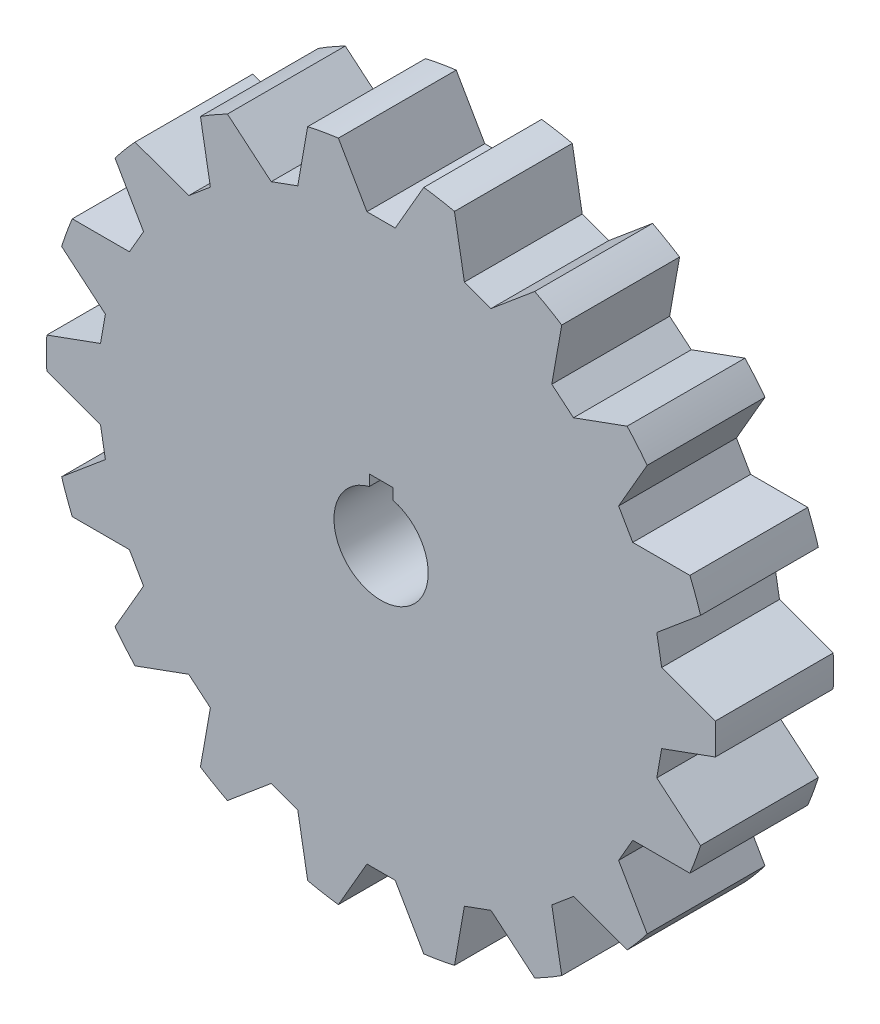
SolidWorks part; units mm, degrees
ref_plane "Front Plane" through (0, 0, 0) normal (0, 0, 1) x (1, 0, 0)
ref_plane "Top Plane" through (0, 0, 0) normal (0, 1, 0) x (1, 0, 0)
ref_plane "Right Plane" through (0, 0, 0) normal (1, 0, 0) x (0, 0, -1)
sketch "Sketch1" plane through (0, 0, 0) normal (0, 0, 1) x (1, 0, 0)
  line L0 (2.5, 9.6825) -> (2.5, 12)
  line L1 (2.5, 12) -> (-2.5, 12)
  line L8 (-2.5, 12) -> (-2.5, 9.6825)
  line L9 (-3, 59.925) -> (3, 59.925)
  line L10 (3, 59.925) -> (9.0591, 70.4197)
  line L12 (-9.0591, 70.4197) -> (-3, 59.925)
  line L13 (23.3146, 55.285) -> (32.5978, 63.0745)
  line L14 (15.5721, 69.2713) -> (17.6765, 57.3371)
  line L15 (17.6765, 57.3371) -> (23.3146, 55.285)
  line L16 (40.8172, 43.9768) -> (52.2046, 48.1215)
  line L17 (38.3252, 59.7677) -> (36.2209, 47.8335)
  line L18 (36.2209, 47.8335) -> (40.8172, 43.9768)
  line L19 (53.3965, 27.3644) -> (65.5148, 27.3644)
  line L20 (56.4557, 43.0553) -> (50.3965, 32.5606)
  line L21 (50.3965, 32.5606) -> (53.3965, 27.3644)
  line L22 (59.5355, 7.4514) -> (70.923, 3.3067)
  line L23 (67.7767, 21.1498) -> (58.4936, 13.3603)
  line L24 (58.4936, 13.3603) -> (59.5355, 7.4514)
  line L25 (58.4936, -13.3603) -> (67.7767, -21.1498)
  line L26 (70.923, -3.3067) -> (59.5355, -7.4514)
  line L27 (59.5355, -7.4514) -> (58.4936, -13.3603)
  line L28 (50.3965, -32.5606) -> (56.4557, -43.0553)
  line L29 (65.5148, -27.3644) -> (53.3965, -27.3644)
  line L30 (53.3965, -27.3644) -> (50.3965, -32.5606)
  line L31 (36.2209, -47.8335) -> (38.3252, -59.7677)
  line L32 (52.2046, -48.1215) -> (40.8172, -43.9768)
  line L33 (40.8172, -43.9768) -> (36.2209, -47.8335)
  line L34 (17.6765, -57.3371) -> (15.5721, -69.2713)
  line L35 (32.5978, -63.0745) -> (23.3146, -55.285)
  line L36 (23.3146, -55.285) -> (17.6765, -57.3371)
  line L37 (-3, -59.925) -> (-9.0591, -70.4197)
  line L38 (9.0591, -70.4197) -> (3, -59.925)
  line L39 (3, -59.925) -> (-3, -59.925)
  line L40 (-23.3146, -55.285) -> (-32.5978, -63.0745)
  line L41 (-15.5721, -69.2713) -> (-17.6765, -57.3371)
  line L42 (-17.6765, -57.3371) -> (-23.3146, -55.285)
  line L43 (-40.8172, -43.9768) -> (-52.2046, -48.1215)
  line L44 (-38.3252, -59.7677) -> (-36.2209, -47.8335)
  line L45 (-36.2209, -47.8335) -> (-40.8172, -43.9768)
  line L46 (-53.3965, -27.3644) -> (-65.5148, -27.3644)
  line L47 (-56.4557, -43.0553) -> (-50.3965, -32.5606)
  line L48 (-50.3965, -32.5606) -> (-53.3965, -27.3644)
  line L49 (-59.5355, -7.4514) -> (-70.923, -3.3067)
  line L50 (-67.7767, -21.1498) -> (-58.4936, -13.3603)
  line L51 (-58.4936, -13.3603) -> (-59.5355, -7.4514)
  line L52 (-58.4936, 13.3603) -> (-67.7767, 21.1498)
  line L53 (-70.923, 3.3067) -> (-59.5355, 7.4514)
  line L54 (-59.5355, 7.4514) -> (-58.4936, 13.3603)
  line L55 (-50.3965, 32.5606) -> (-56.4557, 43.0553)
  line L56 (-65.5148, 27.3644) -> (-53.3965, 27.3644)
  line L57 (-53.3965, 27.3644) -> (-50.3965, 32.5606)
  line L58 (-36.2209, 47.8335) -> (-38.3252, 59.7677)
  line L59 (-52.2046, 48.1215) -> (-40.8172, 43.9768)
  line L60 (-40.8172, 43.9768) -> (-36.2209, 47.8335)
  line L61 (-17.6765, 57.3371) -> (-15.5721, 69.2713)
  line L62 (-32.5978, 63.0745) -> (-23.3146, 55.285)
  line L63 (-23.3146, 55.285) -> (-17.6765, 57.3371)
  line L64 (0, 0) -> (3, 59.925) construction
  arc A1 (-2.5, 9.6825) -> (2.5, 9.6825) centre (0, 0) ccw
  arc A2 (-52.2046, 48.1215) -> (-56.4557, 43.0553) centre (0, 0) ccw
  arc A3 (23.3146, 55.285) -> (17.6765, 57.3371) centre (0, 0) ccw
  arc A4 (40.8172, 43.9768) -> (36.2209, 47.8335) centre (0, 0) ccw
  arc A5 (53.3965, 27.3644) -> (50.3965, 32.5606) centre (0, 0) ccw
  arc A6 (59.5355, 7.4514) -> (58.4936, 13.3603) centre (0, 0) ccw
  arc A7 (58.4936, -13.3603) -> (59.5355, -7.4514) centre (0, 0) ccw
  arc A8 (50.3965, -32.5606) -> (53.3965, -27.3644) centre (0, 0) ccw
  arc A9 (-40.8172, -43.9768) -> (-36.2209, -47.8335) centre (0, 0) ccw
  arc A10 (-53.3965, -27.3644) -> (-50.3965, -32.5606) centre (0, 0) ccw
  arc A11 (-59.5355, -7.4514) -> (-58.4936, -13.3603) centre (0, 0) ccw
  arc A12 (-36.2209, 47.8335) -> (-40.8172, 43.9768) centre (0, 0) ccw
  arc A13 (-17.6765, 57.3371) -> (-23.3146, 55.285) centre (0, 0) ccw
  arc A14 (36.2209, -47.8335) -> (40.8172, -43.9768) centre (0, 0) ccw
  arc A15 (17.6765, -57.3371) -> (23.3146, -55.285) centre (0, 0) ccw
  arc A16 (-3, -59.925) -> (3, -59.925) centre (0, 0) ccw
  arc A17 (-23.3146, -55.285) -> (-17.6765, -57.3371) centre (0, 0) ccw
  arc A18 (-65.5148, 27.3644) -> (-67.7767, 21.1498) centre (0, 0) ccw
  arc A19 (-70.923, 3.3067) -> (-70.923, -3.3067) centre (0, 0) ccw
  arc A20 (-67.7767, -21.1498) -> (-65.5148, -27.3644) centre (0, 0) ccw
  arc A21 (-56.4557, -43.0553) -> (-52.2046, -48.1215) centre (0, 0) ccw
  arc A22 (-38.3252, -59.7677) -> (-32.5978, -63.0745) centre (0, 0) ccw
  arc A23 (-15.5721, -69.2713) -> (-9.0591, -70.4197) centre (0, 0) ccw
  arc A24 (52.2046, -48.1215) -> (56.4557, -43.0553) centre (0, 0) ccw
  arc A25 (32.5978, -63.0745) -> (38.3252, -59.7677) centre (0, 0) ccw
  arc A26 (9.0591, -70.4197) -> (15.5721, -69.2713) centre (0, 0) ccw
  arc A27 (15.5721, 69.2713) -> (9.0591, 70.4197) centre (0, 0) ccw
  arc A28 (38.3252, 59.7677) -> (32.5978, 63.0745) centre (0, 0) ccw
  arc A29 (56.4557, 43.0553) -> (52.2046, 48.1215) centre (0, 0) ccw
  arc A30 (67.7767, 21.1498) -> (65.5148, 27.3644) centre (0, 0) ccw
  arc A31 (70.923, -3.3067) -> (70.923, 3.3067) centre (0, 0) ccw
  arc A32 (65.5148, -27.3644) -> (67.7767, -21.1498) centre (0, 0) ccw
  arc A33 (-9.0591, 70.4197) -> (-15.5721, 69.2713) centre (0, 0) ccw
  arc A34 (-32.5978, 63.0745) -> (-38.3252, 59.7677) centre (0, 0) ccw
  point P11 (0, 59.925)
  point P15 (0, 12)
  dimension "D1" = 142
  dimension "D3" = 20
  dimension "D6" = 5
  dimension "D4" = 12
  dimension "D5" = 60
  dimension "D7" = 6
  dimension "D9" = 60
  dimension "D8" = 18
extrude "Boss-Extrude1" add sketch "Sketch1" against normal blind 25
